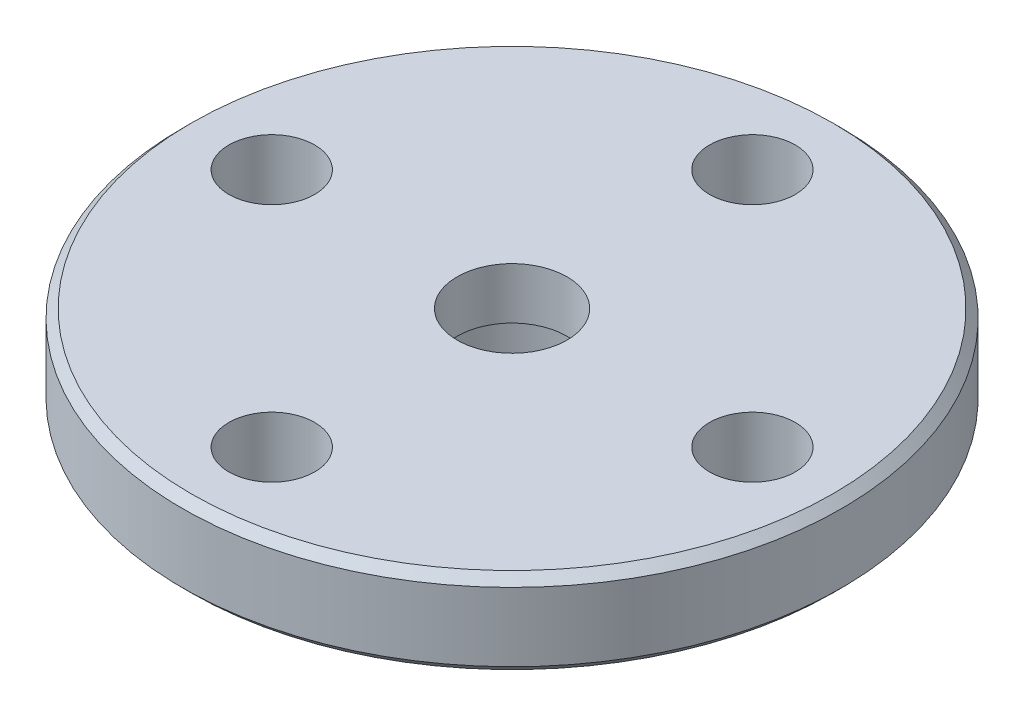
SolidWorks part; units mm, degrees
ref_plane "Front Plane" through (0, 0, 0) normal (0, 0, 1) x (1, 0, 0)
ref_plane "Top Plane" through (0, 0, 0) normal (0, 1, 0) x (1, 0, 0)
ref_plane "Right Plane" through (0, 0, 0) normal (1, 0, 0) x (0, 0, -1)
sketch "Sketch1" plane through (0, 0, 0) normal (0, 0, 1) x (1, 0, 0)
  line L0 (0, 0) -> (0, 5.0113) construction
  line L1 (1.6, 3) -> (1.6, 4.5)
  line L2 (1.6, 4.5) -> (9.35, 4.5)
  line L3 (9.6, 4.25) -> (9.6, 2.25)
  line L4 (9.35, 2) -> (5.3, 2)
  line L5 (5.3, 2) -> (5.3, 0.25)
  line L6 (5.3, 0.25) -> (5.05, 0)
  line L7 (5.05, 0) -> (2.6, 0)
  line L8 (9.6, 2.25) -> (9.35, 2)
  line L9 (1.6, 3) -> (2.6, 3)
  line L10 (9.35, 4.5) -> (9.6, 4.25)
  line L11 (2.6, 3) -> (2.6, 0)
  line L12 (5.175, 0.125) -> (5.3, 0) construction
  dimension "D1" = 19.2
  dimension "D2" = 3.2
  dimension "D3" = 2.5
  dimension "D4" = 2
  dimension "D5" = 10.6
  dimension "D6" = 0.25
  dimension "D7" = 0.25
  dimension "D8" = 1.5
  dimension "D9" = 5.2
revolve "Revolve1" add sketch "Sketch1" angle 360 about L0
sketch "Sketch2" plane through (0, 0, 0) normal (0, 1, 0) x (1, 0, 0)
  line L0 (0, 9.6) -> (0, -9.6) construction
  line L2 (-9.6, 0) -> (9.6, 0) construction
  circle A0 centre (0, 7) radius 1.25
  circle A1 centre (0, -7) radius 1.25
  circle A2 centre (7, 0) radius 1.25
  circle A3 centre (-7, 0) radius 1.25
  circle A4 centre (0, 0) radius 9.6 construction
  point P15 (0, 0)
  point P16 (0, 6.187)
  point P17 (0, 0)
  point P18 (0, -6.5661)
  dimension "D1" = 14
  dimension "D3" = 2.5
  dimension "D2" = 14
extrude "Cut-Extrude1" cut sketch "Sketch2" along normal through all
